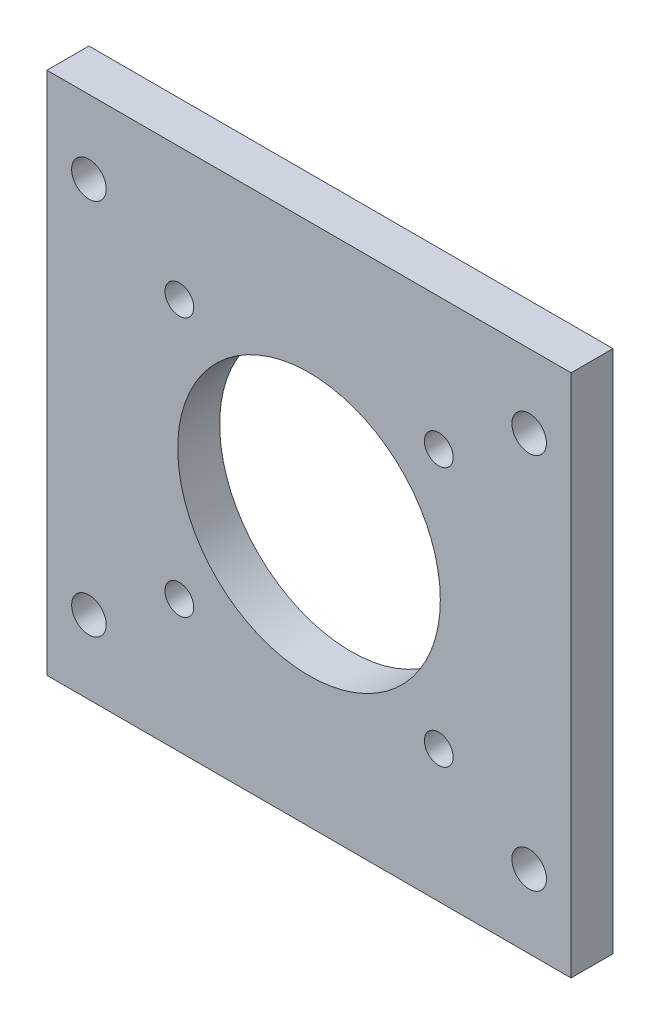
SolidWorks part; units mm, degrees
material "6061-T6 (SS)"
ref_plane "Front Plane" through (0, 0, 0) normal (0, 0, 1) x (1, 0, 0)
ref_plane "Top Plane" through (0, 0, 0) normal (0, 1, 0) x (1, 0, 0)
ref_plane "Right Plane" through (0, 0, 0) normal (1, 0, 0) x (0, 0, -1)
sketch "Sketch1" plane through (0, 0, 0) normal (0, 0, 1) x (1, 0, 0)
  line L1 (-50, -50) -> (50, -50)
  line L2 (-50, -50) -> (-50, 50)
  line L3 (-50, 50) -> (50, 50)
  line L4 (50, -50) -> (50, 50)
  circle A0 centre (0, 0) radius 25.05
  circle A1 centre (-42, -36) radius 3.3
  circle A2 centre (-42, 36) radius 3.3
  circle A3 centre (42, -36) radius 3.3
  circle A4 centre (42, 36) radius 3.3
  circle A5 centre (-24.7487, -24.7487) radius 2.75
  circle A6 centre (-24.7487, 24.7487) radius 2.75
  circle A7 centre (24.7487, -24.7487) radius 2.75
  circle A8 centre (24.7487, 24.7487) radius 2.75
extrude "Motor_Adapter_Plate" add sketch "Sketch1" along normal blind 8
